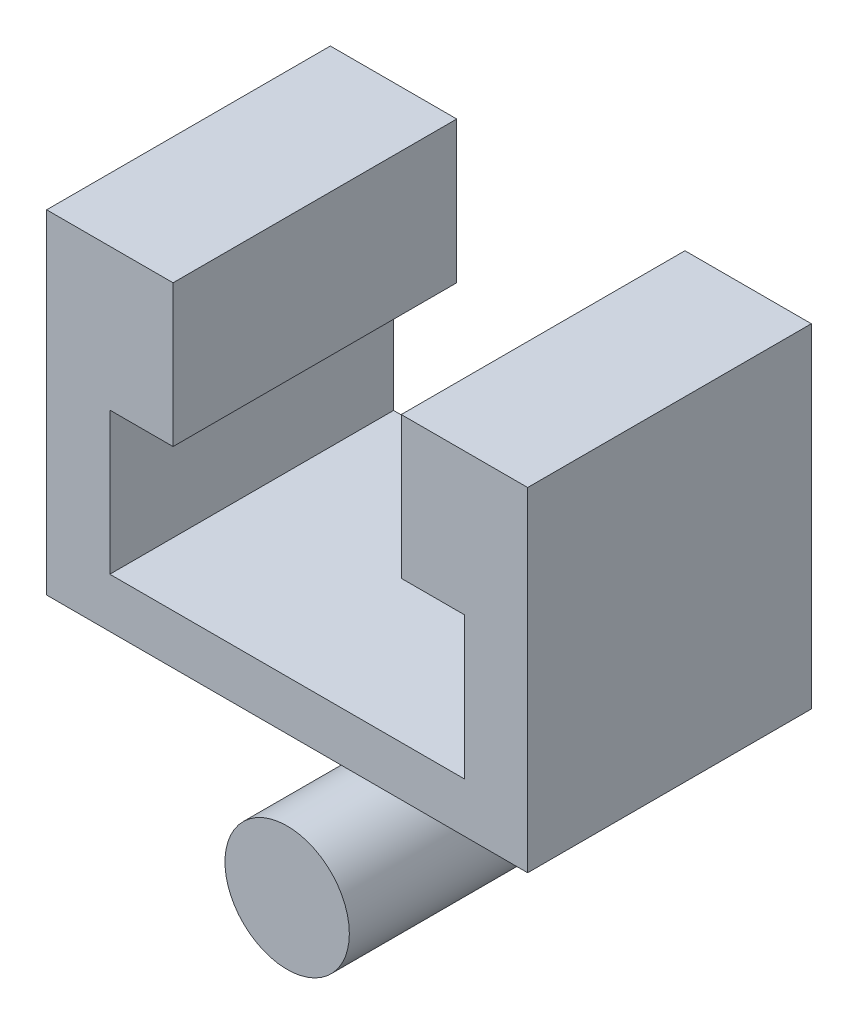
SolidWorks part; units mm, degrees
material "ASTM A36 Steel"
ref_plane "Front Plane" through (0, 0, 0) normal (0, 0, 1) x (1, 0, 0)
ref_plane "Top Plane" through (0, 0, 0) normal (0, 1, 0) x (1, 0, 0)
ref_plane "Right Plane" through (0, 0, 0) normal (1, 0, 0) x (0, 0, -1)
sketch "Sketch1" plane through (0, 0, 0) normal (0, 0, 1) x (1, 0, 0)
  line L0 (-11.1361, 0) -> (-11.1361, 25.4)
  line L1 (-11.1361, 25.4) -> (11.1361, 25.4)
  line L2 (11.1361, 25.4) -> (11.1361, 0)
  arc A0 (11.1361, 0) -> (-11.1361, 0) centre (0, 0) ccw
  arc A1 (11.1361, 0) -> (-11.1361, 0) centre (0, 0) ccw
  dimension "D1" = 22.2722
  dimension "D2" = 25.4
extrude "Boss-Extrude1" add sketch "Sketch1" along normal blind 2.5218 contours A1 L0 L1 L2
sketch "Sketch2" plane through (0, 0, 0) normal (0, 0, 1) x (1, 0, 0)
  circle A0 centre (0, 0) radius 11.1361
  dimension "D1" = 22.2722
extrude "Boss-Extrude2" add sketch "Sketch2" along normal blind 50.8
sketch "Sketch3" plane through (0, 0, 0) normal (0, 0, 1) x (1, 0, 0)
  line L0 (-43.0685, 25.4) -> (43.0685, 25.4)
  line L1 (43.0685, 25.4) -> (43.0685, 85.1481)
  line L2 (43.0685, 85.1481) -> (-43.0685, 85.1481)
  line L3 (-43.0685, 85.1481) -> (-43.0685, 25.4)
  point P3 (0, 25.4)
  dimension "D1" = 86.137
  dimension "D2" = 59.7481
extrude "Boss-Extrude3" add sketch "Sketch3" along normal blind 50.8
sketch "Sketch4" plane through (0, 0, 50.8) normal (0, 0, 1) x (1, 0, 0)
  line L0 (20.4315, 85.1481) -> (20.4315, 59.7481)
  line L1 (43.0685, 85.1481) -> (-43.0685, 85.1481) construction
  line L2 (20.4315, 59.7481) -> (31.75, 59.7481)
  line L3 (31.75, 59.7481) -> (31.75, 34.29)
  line L4 (31.75, 34.29) -> (-31.75, 34.29)
  line L5 (-31.75, 34.29) -> (-31.75, 59.7481)
  line L6 (-31.75, 59.7481) -> (-20.4315, 59.7481)
  line L7 (-20.4315, 59.7481) -> (-20.4315, 85.1481)
  line L8 (-20.4315, 85.1481) -> (20.4315, 85.1481)
  line L9 (43.0685, 25.4) -> (43.0685, 85.1481) construction
  line L10 (-43.0685, 85.1481) -> (-43.0685, 25.4) construction
  line L12 (-43.0685, 25.4) -> (43.0685, 25.4) construction
  dimension "D1" = 22.637
  dimension "D2" = 11.3185
  dimension "D3" = 11.3185
  dimension "D4" = 22.637
  dimension "D6" = 25.4
  dimension "D7" = 25.4
  dimension "D5" = 8.89
extrude "Cut-Extrude1" cut sketch "Sketch4" against normal through all contours L8 L0 L2 L3 L4 L5 L6 L7
ref_plane "Plane1" through (0, 0, 12.7) normal (0, 0, -1) x (-1, 0, 0)
mirror "Mirror1" about plane through (0, 0, 12.7) normal (0, 0, -1) of "Boss-Extrude1"
equation "\"F\"= 600'Applied Load [lbf]"
equation "\"P\"= \"F\" / 2'Symmetric Leg Force [lbf]"
equation "\"Ys\"= 36259.43'Material Yield Strength (ASTM A36) [psi]"
equation "\"E\"= 29007547.53'Elastic Modulus (ASTM A36) [psi]"
equation "\"Ns\"= 4'Factor of Safety"
equation "\"sigma_allow\"= \"Ys\" / \"Ns\"'Allowable Bending/Tensile Stress [psi]"
equation "\"delta_max\"= 0.005'Maximum Deflection Limit [in]"
equation "\"L_A\"= 2.00'Feature A Pin Length [in]"
equation "\"d_stress_A\"= ( ( 32 * \"P\" * \"L_A\" ) / ( pi * \"sigma_allow\" ) ) ^ ( 1 / 3 )'Feature A Minimum Stress Diameter [in]"
equation "\"d_stiff_A\"= ( ( 64 * \"P\" * ( \"L_A\" ^ 3 ) ) / ( 3 * pi * \"E\" * \"delta_max\" ) ) ^ ( 1 / 4 )'Feature A Minimum Stiffness Diameter [in]"
equation "\"d_A\"= 1.000'Feature A Selected Nominal Diameter [in]"
equation "\"w_B\"= \"d_A\"'Feature B Width (Tied to Feature A Pin Dia) [in]"
equation "\"L_B\"= 2.00'Feature B Link Length [in]"
equation "\"t_stress_B\"= \"P\" / ( \"w_B\" * \"sigma_allow\" )'Feature B Minimum Tensile Thickness [in]"
equation "\"t_stiff_B\"= ( \"P\" * \"L_B\" ) / ( \"w_B\" * \"E\" * \"delta_max\" )'Feature B Minimum Stiffness Thickness [in]"
equation "\"t_B\"= 0.250'Feature B Selected Nominal Thickness [in]"
equation "\"L_C\"= 2.5'Feature C Beam Span Length [in]"
equation "\"w_C\"= 1.00'Feature C Beam Cross-Section Width [in]"
equation "\"h_stress_C\"= ( ( 1.5 * \"P\" * \"L_C\" ) / ( \"w_C\" * \"sigma_allow\" ) ) ^ ( 1 / 2 )'Feature C Minimum Bending Height [in]"
equation "\"h_stiff_C\"= ( ( \"P\" * ( \"L_C\" ^ 3 ) ) / ( 4 * \"w_C\" * \"E\" * \"delta_max\" ) ) ^ ( 1 / 3 )'Feature C Minimum Stiffness Height [in]"
equation "\"h_C\"= 0.375'Feature C Selected Nominal Height [in]"
equation "\"P_D\"= \"P\" / 2'Feature D Reaction Load from Feature C [lbf]"
equation "\"L_D\"= 2.00'Feature D Web Cantilever Length [in]"
equation "\"w_D\"= 1.00'Feature D Web Width [in]"
equation "\"t_stress_D\"= ( ( 6 * \"P_D\" * \"L_D\" ) / ( \"w_D\" * \"sigma_allow\" ) ) ^ ( 1 / 2 )'Feature D Minimum Bending Thickness [in]"
equation "\"t_stiff_D\"= ( ( 4 * \"P_D\" * ( \"L_D\" ^ 3 ) ) / ( \"w_D\" * \"E\" * \"delta_max\" ) ) ^ ( 1 / 3 )'Feature D Minimum Stiffness Thickness [in]"
equation "\"t_D\"= 0.500'Feature D Selected Nominal Thickness [in]"
equation "\"P_E\"= \"P_D\"'Feature E Transferred Flange Load [lbf]"
equation "\"L_E\"= 2.00'Feature E Flange Overhang Span [in]"
equation "\"w_E\"= 1.00'Feature E Flange Width [in]"
equation "\"h_stress_E\"= ( ( 6 * \"P_E\" * \"L_E\" ) / ( \"w_E\" * \"sigma_allow\" ) ) ^ ( 1 / 2 )'Feature E Minimum Bending Thickness [in]"
equation "\"h_stiff_E\"= ( ( 4 * \"P_E\" * ( \"L_E\" ^ 3 ) ) / ( \"w_E\" * \"E\" * \"delta_max\" ) ) ^ ( 1 / 3 )'Feature E Minimum Stiffness Thickness [in]"
equation "\"h_E\"= 0.500'Feature E Selected Nominal Thickness [in]"
equation "\"D1@Sketch1\"=\"d_stress_A\""
equation "\"D1@Boss-Extrude1\"=\"t_stress_B\"*3"
equation "\"D1@Sketch2\"=\"d_stress_A\""
equation "\"D1@Boss-Extrude2\"=\"L_A\""
equation "\"D1@Sketch3\"=\"L_C\"+2*(\"t_stress_D\")"
equation "\"D2@Sketch3\"=\"h_stress_C\" + \"w_D\"+\"w_E\""
equation "\"D7@Sketch4\"=\"w_E\""
equation "\"D6@Sketch4\"=\"w_E\""
equation "\"D1@Sketch4\"=\"t_stress_D\"+\"h_stress_E\""
equation "\"D4@Sketch4\"=\"t_stress_D\"+\"h_stress_E\""
equation "\"D2@Sketch4\"=\"t_stress_D\""
equation "\"D3@Sketch4\"=\"t_stress_D\""
equation "\"D1@Boss-Extrude3\"=\"L_D\""
